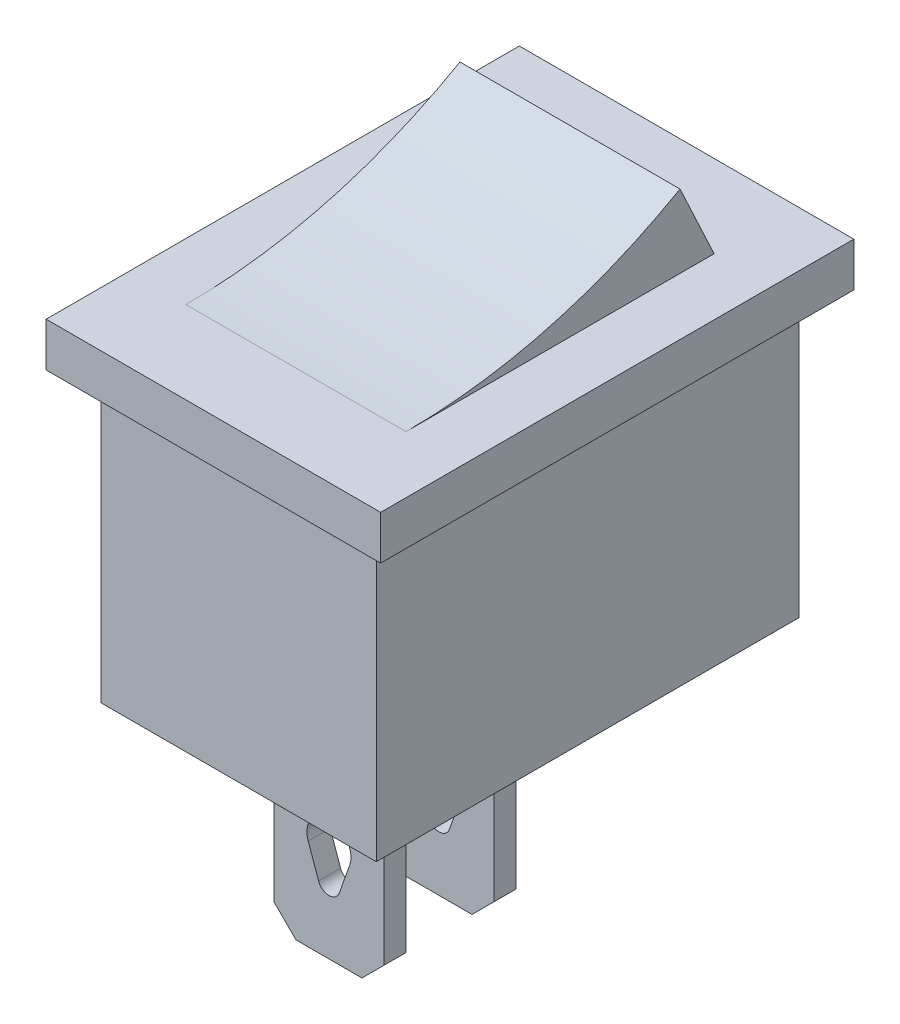
SolidWorks part; units mm, degrees
ref_plane "Спереди" through (0, 0, 0) normal (0, 0, 1) x (1, 0, 0)
ref_plane "Сверху" through (0, 0, 0) normal (0, 1, 0) x (1, 0, 0)
ref_plane "Справа" through (0, 0, 0) normal (1, 0, 0) x (0, 0, -1)
sketch "Эскиз1" plane through (0, 0, 0) normal (0, 1, 0) x (1, 0, 0)
  line L1 (-6.25, -9.6) -> (6.25, -9.6)
  line L2 (-6.25, -9.6) -> (-6.25, 9.6)
  line L3 (-6.25, 9.6) -> (6.25, 9.6)
  line L4 (6.25, -9.6) -> (6.25, 9.6)
  line L5 (-6.25, -9.6) -> (6.25, 9.6) construction
  line L6 (-6.25, 9.6) -> (6.25, -9.6) construction
  point P0 (0, 0)
  dimension "D1" = 12.5
  dimension "D2" = 19.2
extrude "Бобышка-Вытянуть1" add sketch "Эскиз1" along normal blind 13
sketch "Эскиз2" plane through (0, 0, 0) normal (0, -1, 0) x (1, 0, 0)
  line L0 (-2.5, -0.5) -> (-2.5, 0.5)
  line L1 (-2.5, 4.5) -> (2.5, 4.5)
  line L2 (-2.5, 4.5) -> (-2.5, 5.5)
  line L3 (-2.5, 5.5) -> (2.5, 5.5)
  line L4 (2.5, 4.5) -> (2.5, 5.5)
  line L5 (-2.5, 4.5) -> (2.5, 5.5) construction
  line L6 (-2.5, 5.5) -> (2.5, 4.5) construction
  line L7 (-2.5, 0.5) -> (2.5, 0.5)
  line L8 (2.5, -0.5) -> (2.5, 0.5)
  line L9 (-2.5, -0.5) -> (2.5, -0.5)
  line L10 (-2.5, 0.5) -> (2.5, -0.5) construction
  line L11 (-2.5, -0.5) -> (2.5, 0.5) construction
  line L12 (-2.5, 4.5) -> (-2.5, -0.5) construction
  point P0 (0, 5)
  point P5 (0, 0)
  dimension "D1" = 1
  dimension "D2" = 5
  dimension "D4" = 5
  dimension "D3" = 2
extrude "Бобышка-Вытянуть2" add sketch "Эскиз2" along normal blind 9
chamfer "Фаска1" distance 1 angle 45 4 edges at (2.5, -9, 0) (-2.5, -9, 0) (-2.5, -9, 5) (2.5, -9, 5)
sketch "Эскиз3" plane through (0, 0, -0.5) normal (0, 0, -1) x (-1, 0, 0)
  line L0 (1.0205, -6.5) -> (-0.7522, -6.5) construction
  line L1 (1.2473, -3.5) -> (-1.5556, -3.5) construction
  line L2 (0.9428, -4.8333) -> (0.4714, -6.1667)
  line L3 (-0.4714, -6.1667) -> (-0.9428, -4.8333)
  line L5 (1.5, -9) -> (-1.5, -9) construction
  arc A0 (0.9428, -4.8333) -> (-0.9428, -4.8333) centre (0, -4.5) ccw
  arc A1 (-0.4714, -6.1667) -> (0.4714, -6.1667) centre (0, -6) ccw
  point P13 (-1.4404, -3.5677)
  point P14 (-0.4962, -6.6192)
  point P15 (0, 0)
  point P16 (0, 0)
  point P18 (0, 0)
  dimension "D1" = 1
  dimension "D2" = 2
  dimension "D4" = 2.5
  dimension "D3" = 3
extrude "Вырез-Вытянуть1" cut sketch "Эскиз3" against normal through all both and the other way through all
sketch "Эскиз4" plane through (0, 13, 0) normal (0, 1, 0) x (1, 0, 0)
  line L1 (7.6, -10.75) -> (-7.6, -10.75)
  line L2 (7.6, -10.75) -> (7.6, 10.75)
  line L3 (7.6, 10.75) -> (-7.6, 10.75)
  line L4 (-7.6, -10.75) -> (-7.6, 10.75)
  line L5 (7.6, -10.75) -> (-7.6, 10.75) construction
  line L6 (7.6, 10.75) -> (-7.6, -10.75) construction
  point P0 (0, 0)
  dimension "D1" = 15.2
  dimension "D2" = 21.5
extrude "Бобышка-Вытянуть3" add sketch "Эскиз4" along normal blind 2
sketch "Эскиз5" plane through (0, 0, 0) normal (1, 0, 0) x (0, 0, -1)
  line L0 (-7, 15) -> (7, 15)
  line L1 (7, 15) -> (5.4513, 18.3213)
  line L2 (-10.75, 15) -> (10.75, 15) construction
  arc A0 (-7, 15) -> (5.4513, 18.3213) centre (-7, 40) ccw
  point P4 (-4.0909, 17.8614)
  point P5 (0, 15)
  dimension "D1" = 50
  dimension "D2" = 65
  dimension "D3" = 14
extrude "Бобышка-Вытянуть4" add sketch "Эскиз5" along normal mid plane 10
